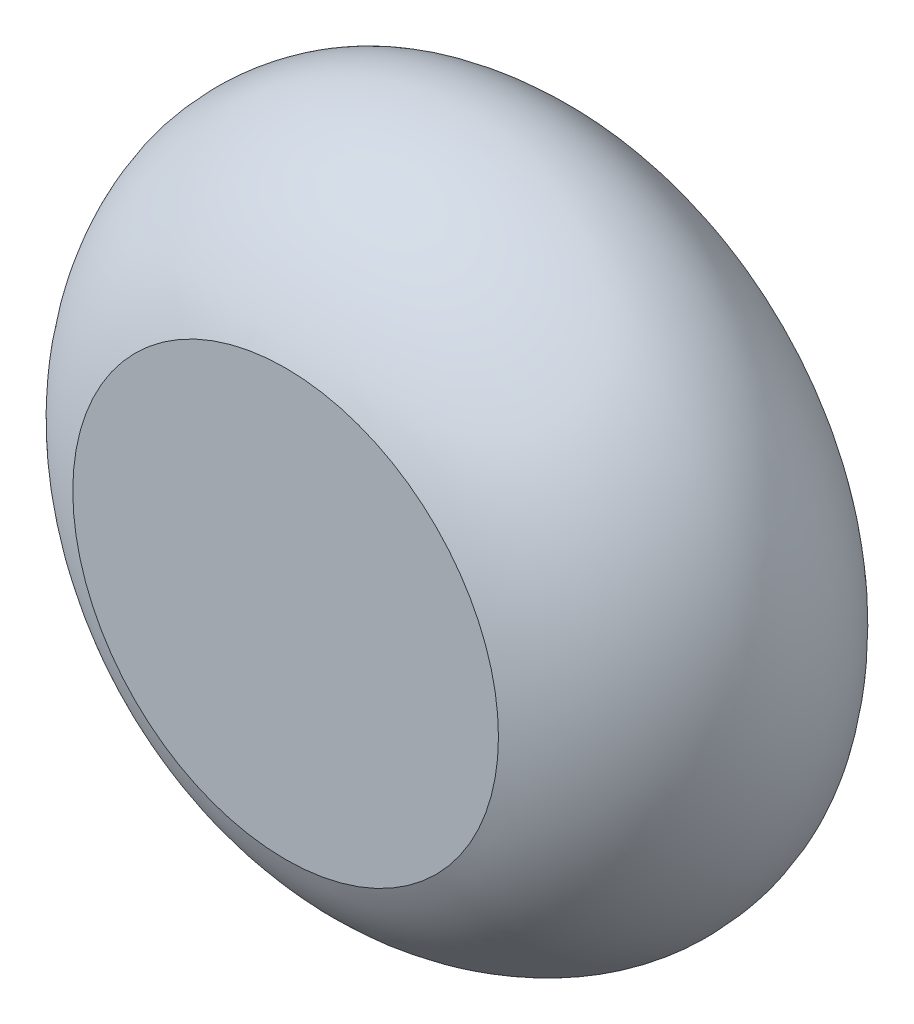
SolidWorks part; units mm, degrees
ref_plane "Front Plane" through (0, 0, 0) normal (0, 0, 1) x (1, 0, 0)
ref_plane "Top Plane" through (0, 0, 0) normal (0, 1, 0) x (1, 0, 0)
ref_plane "Right Plane" through (0, 0, 0) normal (1, 0, 0) x (0, 0, -1)
sketch "Sketch1" plane through (0, 0, 0) normal (0, 1, 0) x (1, 0, 0)
  line B0 (-30.7443, -6.5243) -> (1.776, -6.5243)
  line B1 (-31.7507, -11.5243) -> (1.776, -11.5243)
  arc B2 (-23.4913, 42.3911) -> (-22.487, 42.5339) centre (-20.5194, 25.0897) cw
  spline B3 degree 3 poles (-22.6544, 37.4616) (-23.2936, 37.3531) (-24.562, 37.1307) (-27.1597, 36.6226) (-31.735, 35.5249) (-36.195, 33.7727) (-39.6153, 31.4636) (-41.2251, 30.1243) (-42.6961, 28.6534) (-44.4406, 26.6637) (-46.0128, 24.4443) (-47.133, 21.7298) (-47.846, 18.7246) (-48.0322, 14.7525) (-47.1177, 10.6043) (-45.5267, 6.9734) (-43.4305, 3.4775) (-40.8177, 0.2841) (-37.7679, -2.5154) (-34.9434, -4.444) (-32.5631, -5.7284) (-31.3566, -6.2674) (-30.7443, -6.5243) knots 0 0 0 0 0.031353 0.062705 0.125411 0.250821 0.282174 0.313527 0.344879 0.376232 0.438937 0.47029 0.501643 0.564348 0.627054 0.689759 0.752464 0.81517 0.877875 0.94058 0.971933 1.003286 1.003286 1.003286 1.003286
  spline B4 degree 3 poles (-23.4913, 42.3911) (-24.1667, 42.2764) (-25.4966, 42.0432) (-28.3038, 41.4929) (-31.933, 40.6184) (-35.6546, 39.3364) (-38.6123, 37.9578) (-40.7949, 36.7189) (-42.9206, 35.2444) (-44.9198, 33.5259) (-46.6478, 31.7467) (-48.1477, 30.0024) (-49.6804, 27.9105) (-51.0655, 25.4388) (-52.1381, 22.5105) (-52.728, 19.5401) (-52.9528, 16.5705) (-52.8092, 13.6005) (-52.2979, 10.829) (-51.5149, 8.3125) (-50.5854, 6.0844) (-49.1679, 3.2445) (-46.9745, -0.1833) (-43.747, -3.9049) (-40.6312, -6.5869) (-37.9473, -8.4319) (-36.2028, -9.4547) (-34.7808, -10.1899) (-33.8729, -10.6187) (-33.2497, -10.8939) (-32.866, -11.0566) (-32.4381, -11.2355) (-32.0507, -11.3984) (-31.7507, -11.5243) knots 0 0 0 0 0.031866 0.063732 0.127464 0.191196 0.223062 0.254928 0.286794 0.318661 0.350527 0.382393 0.414259 0.446125 0.477991 0.509857 0.541723 0.573589 0.605455 0.637321 0.669187 0.701053 0.764785 0.828517 0.89225 0.924116 0.955982 0.971915 0.987848 0.995814 0.999797 1.003781 1.019714 1.019714 1.019714 1.019714
  line B5 (-22.487, 42.5339) -> (-22.6544, 37.4616)
  line B6 (1.776, -6.5243) -> (1.776, -11.5243)
sketch_block_instance "outlineOfHome-1"
sketch_block "outlineOfHome"
revolve "Revolve1" add sketch "Sketch1" angle 360 about L4
